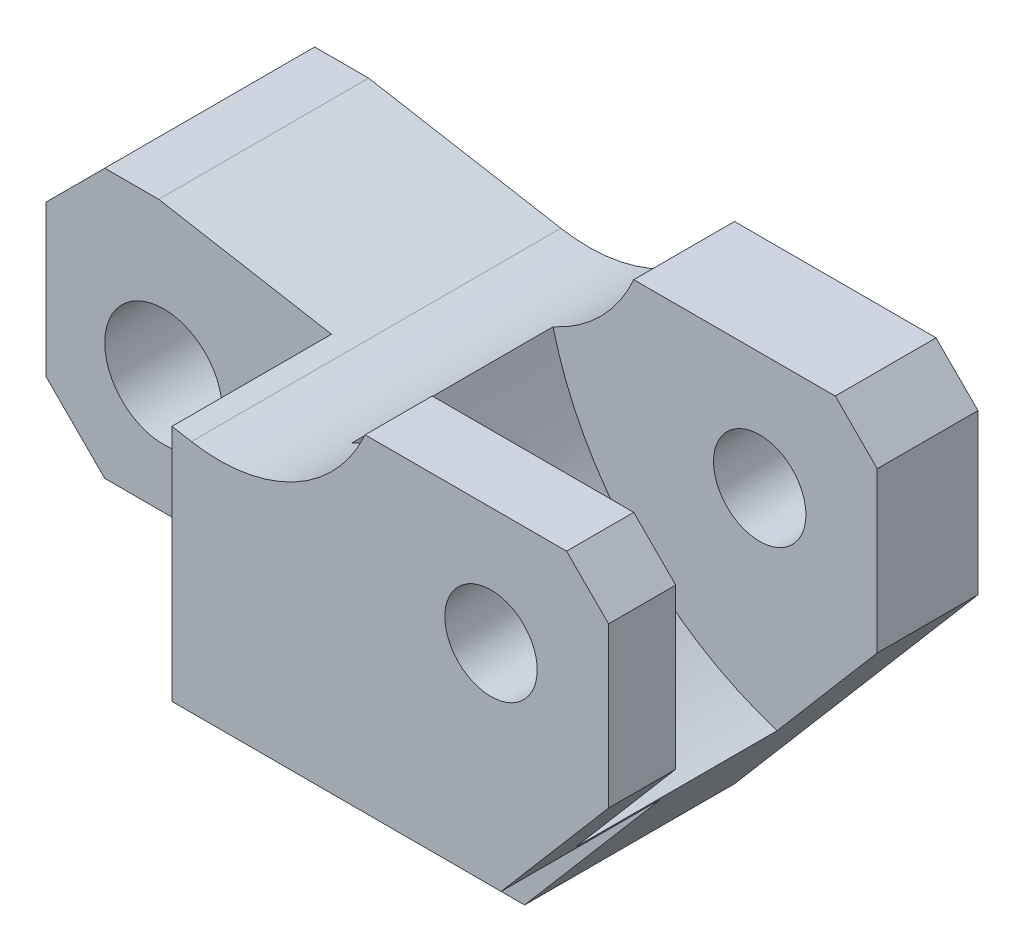
SolidWorks part; units mm, degrees
material "AISI 1020"
ref_plane "Front Plane" through (0, 0, 0) normal (0, 0, 1) x (1, 0, 0)
ref_plane "Top Plane" through (0, 0, 0) normal (0, 1, 0) x (1, 0, 0)
ref_plane "Right Plane" through (0, 0, 0) normal (1, 0, 0) x (0, 0, -1)
sketch "Sketch1" plane through (0, 0, 0) normal (0, 0, 1) x (1, 0, 0)
  line L0 (0, 0) -> (-7, 7)
  line L1 (-7, 7) -> (-7, 25)
  line L2 (-7, 25) -> (0, 32)
  line L3 (0, 32) -> (6.4231, 32)
  line L4 (50, 39) -> (74, 39)
  line L5 (74, 39) -> (79, 34)
  line L6 (79, 34) -> (79, 15)
  line L7 (79, 15) -> (50, -19)
  line L8 (50, -19) -> (44.7881, -19)
  line L10 (32.9488, 0) -> (0, 0)
  line L11 (-7, 14) -> (7, 14) construction
  line L12 (66.2059, -19) -> (66.2059, 0) construction
  line L13 (6.4231, 32) -> (16.9623, 32) construction
  line L14 (6.4231, 32) -> (29.3194, 27.9628)
  circle A0 centre (7, 14) radius 7
  arc A1 (37.8933, -4.2566) -> (32.9488, 0) centre (32.9488, -5) ccw
  arc A2 (44.7881, -19) -> (37.8933, -4.2566) centre (66.2059, 0) cw
  arc A3 (50, 39) -> (29.3194, 27.9628) centre (32.6187, 46.6741) cw
  point P26 (66.2059, 0)
  dimension "D5" = 45
  dimension "D17" = 5
  dimension "D20" = 10
  dimension "D21" = 19
  dimension "D1" = 7
  dimension "D2" = 32
  dimension "D3" = 14
  dimension "D4" = 14
  dimension "D6" = 19
  dimension "D7" = 14
  dimension "D8" = 7
  dimension "D9" = 45
  dimension "D10" = 14
  dimension "D11" = 29
  dimension "D12" = 45
  dimension "D13" = 5
  dimension "D14" = 24
  dimension "D15" = 86
  dimension "D16" = 58
  dimension "D18" = 19
  dimension "D19" = 29
extrude "Boss-Extrude1" add sketch "Sketch1" along normal blind 44
sketch "Sketch2" plane through (0, 0, 0) normal (0, 0, 1) x (1, 0, 0)
  line L0 (79, 39) -> (79, -0.8037) construction
  arc A0 (79, -0.8037) -> (37.7512, 28.3804) centre (79, 42.939) cw
  arc A1 (29.3194, 27.9628) -> (50, 39) centre (32.6187, 46.6741) ccw construction
ref_plane "Plane6" through (79, 0, 0) normal (1, 0, 0) x (0, 0, -1)
sketch "Sketch70" plane through (79, 0, 0) normal (1, 0, 0) x (0, 0, -1)
  line L0 (-44, 39) -> (0, 39) construction
  line L1 (-36, 39) -> (-12, 39)
  line L2 (-36, 39) -> (-36, -0.8037)
  line L3 (-36, -0.8037) -> (-12, -0.8037)
  line L4 (-12, 39) -> (-12, -0.8037)
  line L5 (-36, 39) -> (-12, -0.8037) construction
  line L6 (-36, -0.8037) -> (-12, 39) construction
  line L7 (-44, 15) -> (-44, 34) construction
  line L8 (0, 7) -> (0, 25) construction
  point P4 (-24, 19.0982)
  dimension "D1" = 12
  dimension "D2" = 24
revolve "Cut-Revolve3" cut sketch "Sketch70" angle 360 about L1
ref_plane "Plane8" through (0, 39, 0) normal (0, 1, 0) x (1, 0, 0)
sketch "Sketch71" plane through (0, 39, 0) normal (0, 1, 0) x (1, 0, 0)
  line L0 (-7, -44) -> (-7, 0) construction
  line L1 (-7, -25) -> (27, -25)
  line L2 (-7, -25) -> (-7, -44)
  line L3 (-7, -44) -> (27, -44)
  line L4 (27, -25) -> (27, -44)
  line L5 (-7, -25) -> (27, -44) construction
  line L6 (-7, -44) -> (27, -25) construction
  line L7 (29.3194, -44) -> (6.4231, -44) construction
  point P4 (10, -34.5)
  dimension "D1" = 19
  dimension "D2" = 34
extrude "Cut-Extrude1" cut sketch "Sketch71" against normal blind 43
sketch "Sketch73" plane through (0, 0, 0) normal (0, 0, 1) x (1, 0, 0)
  line L0 (50, 39) -> (74, 39) construction
  line L1 (79, 34) -> (79, 15) construction
  circle A0 centre (65, 25) radius 5.5
  point P0 (65, 25)
  dimension "D1" = 14
  dimension "D2" = 14
extrude "Cut-Extrude3" cut sketch "Sketch73" along normal through all contours A0
sketch "Sketch75" plane through (79, 0, 0) normal (1, 0, 0) x (0, 0, -1)
  line L1 (-44, -19) -> (-25, -19)
  line L2 (-44, -19) -> (-44, 0)
  line L3 (-44, 0) -> (-25, 0)
  line L4 (-25, -19) -> (-25, 0)
  line L5 (-44, -19) -> (-25, 0) construction
  line L6 (-44, 0) -> (-25, -19) construction
  point P4 (-34.5, -9.5)
  dimension "D1" = 19
  dimension "D2" = 19
extrude "Cut-Extrude4" cut sketch "Sketch75" against normal through all
